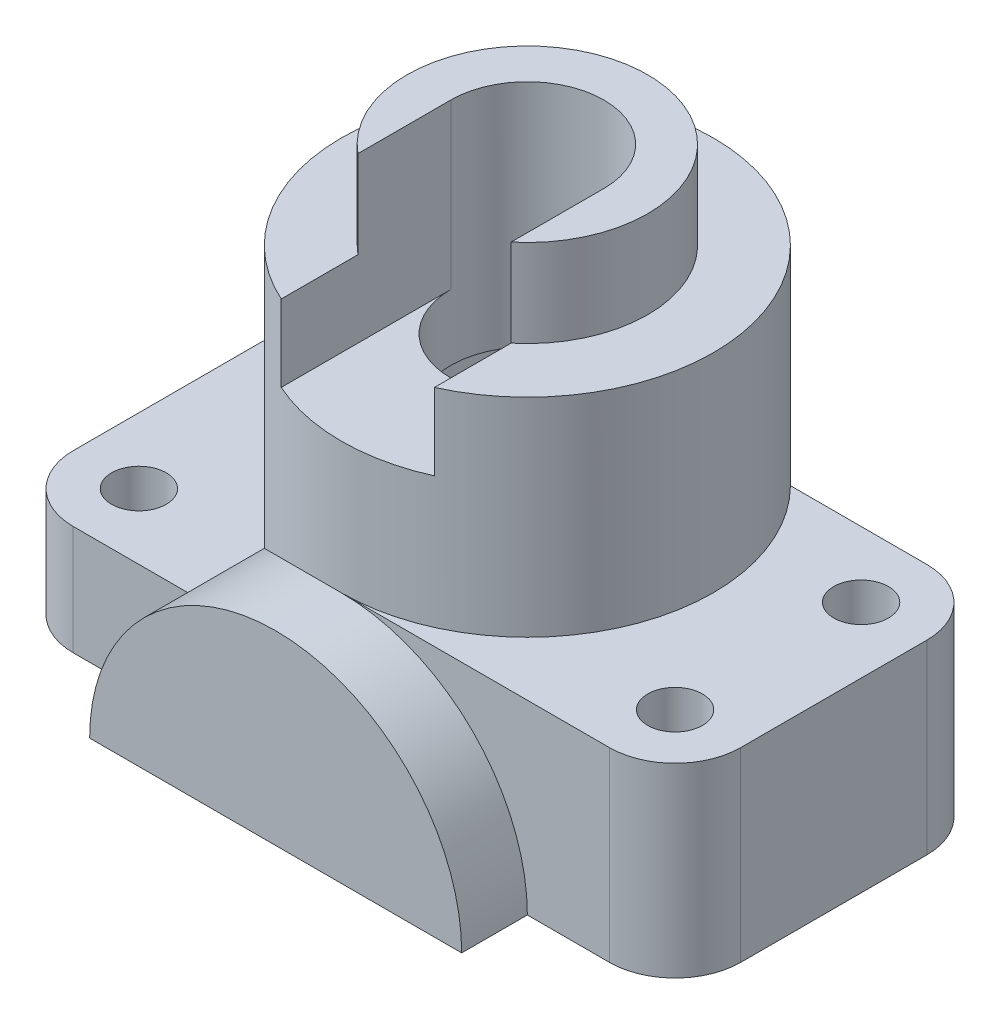
SolidWorks part; units mm, degrees
ref_plane "前视基准面" through (0, 0, 0) normal (0, 0, 1) x (1, 0, 0)
ref_plane "上视基准面" through (0, 0, 0) normal (0, 1, 0) x (1, 0, 0)
ref_plane "右视基准面" through (0, 0, 0) normal (1, 0, 0) x (0, 0, -1)
sketch "草图2" plane through (0, 0, 0) normal (0, 1, 0) x (1, 0, 0)
  circle A0 centre (0, 0) radius 17
  dimension "D1" = 34
extrude "凸台-拉伸1" add sketch "草图2" along normal blind 36
ref_plane "基准面5" through (0, 0, 23) normal (0, 0, 1) x (1, 0, 0)
ref_plane "基准面4" through (0, 44, 0) normal (0, 1, 0) x (1, 0, 0)
sketch "草图4" plane through (0, 44, 0) normal (0, 1, 0) x (1, 0, 0)
  circle A0 centre (0, 0) radius 11
  dimension "D1" = 22
extrude "凸台-拉伸3" add sketch "草图4" against normal up to next
sketch "草图5" plane through (0, 44, 0) normal (0, 1, 0) x (1, 0, 0)
  circle A0 centre (0, 0) radius 7
  dimension "D1" = 14
extrude "切除-拉伸1" cut sketch "草图5" against normal blind 21
sketch "草图6" plane through (0, 0, 0) normal (0, 0, 1) x (1, 0, 0)
  line L0 (0, 0) -> (0, 36.7083) construction
  line L1 (22, 44) -> (-22, 44) construction
  line L2 (-7, 44) -> (7, 44)
  line L3 (-7, 44) -> (-7, 29)
  line L4 (-7, 29) -> (7, 29)
  line L5 (7, 44) -> (7, 29)
  line L6 (-7, 44) -> (7, 29) construction
  line L7 (-7, 29) -> (7, 44) construction
  point P1 (0, 36.5)
  dimension "D1" = 15
  dimension "D2" = 14
extrude "切除-拉伸2" cut sketch "草图6" along normal blind 21
sketch "草图7" plane through (0, 0, 23) normal (0, 0, 1) x (1, 0, 0)
  line L0 (-17, 0) -> (17, 0)
  arc A0 (17, 0) -> (-17, 0) centre (0, 0) ccw
  dimension "D1" = 34
extrude "凸台-拉伸5" add sketch "草图7" against normal blind 23
sketch "草图8" plane through (0, 0, 0) normal (0, 1, 0) x (1, 0, 0)
  line L0 (0, 12) -> (0, -17)
  line L1 (0, -17) -> (24.5, -17)
  line L3 (0, 12) -> (24.5, 12)
  line L4 (30.5, -11) -> (30.5, 6)
  line L7 (28.0515, -15.836) -> (30.5, -17) construction
  line L8 (28.0515, 10.836) -> (30.5, 12) construction
  arc A2 (24.5, -17) -> (30.5, -11) centre (24.5, -11) ccw
  arc A3 (30.5, 6) -> (24.5, 12) centre (24.5, 6) ccw
  circle A5 centre (24.5, 6) radius 2.5
  circle A6 centre (24.5, -11) radius 2.5
  point P2 (28.7426, 10.2426)
  dimension "D1" = 30.5
  dimension "D2" = 29
  dimension "D5" = 17
extrude "凸台-拉伸6" add sketch "草图8" along normal blind 17
sketch "草图9" plane through (0, 0, 0) normal (0, 1, 0) x (1, 0, 0)
  line L0 (0, 12) -> (0, -17)
  line L1 (-24.5, -17) -> (0, -17)
  line L2 (-30.5, -11) -> (-30.5, 6)
  line L3 (-24.5, 12) -> (0, 12)
  line L5 (-30.5, -17) -> (-28.0515, -15.836) construction
  line L6 (-30.5, 12) -> (-28.0515, 10.836) construction
  arc A0 (-30.5, 6) -> (-24.5, 12) centre (-24.5, 6) cw
  arc A1 (-30.5, -11) -> (-24.5, -17) centre (-24.5, -11) ccw
  circle A4 centre (-24.5, 6) radius 2.5
  circle A7 centre (-24.5, -11) radius 2.5
  dimension "D2" = 5
  dimension "D1" = 29
  dimension "D3" = 30.5
  dimension "D4" = 17
extrude "凸台-拉伸7" add sketch "草图9" along normal blind 10
sketch "草图10" plane through (0, 0, 0) normal (0, 1, 0) x (1, 0, 0)
  line L0 (0, 0) -> (42.1296, 0) construction
  line L1 (-12.0416, 12) -> (-12.0416, 0)
  line L2 (12.0416, 12) -> (12.0416, 0)
  arc A3 (-12.0416, 0) -> (12.0416, 0) centre (0, 0) ccw
  arc A4 (12.0416, 12) -> (-12.0416, 12) centre (0, 0) ccw
extrude "切除-拉伸3" cut sketch "草图10" along normal blind 23
